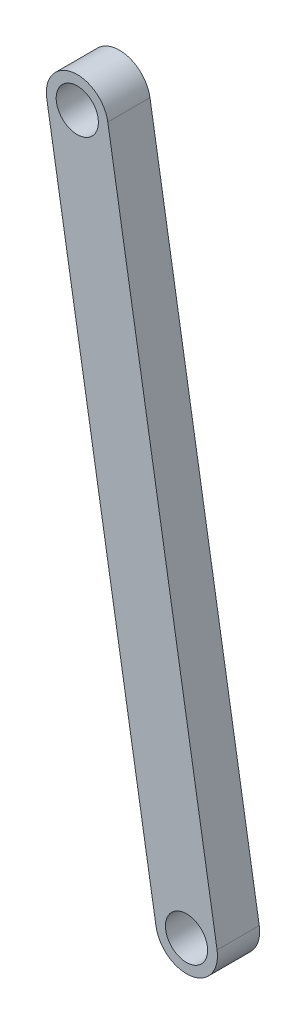
SolidWorks part; units mm, degrees
ref_plane "Plan de face" through (0, 0, 0) normal (0, 0, 1) x (1, 0, 0)
ref_plane "Plan de dessus" through (0, 0, 0) normal (0, 1, 0) x (1, 0, 0)
ref_plane "Plan de droite" through (0, 0, 0) normal (1, 0, 0) x (0, 0, -1)
sketch "Esquisse1" plane through (0, 0, 0) normal (0, 0, 1) x (1, 0, 0)
  line L0 (65.4807, 459.465) -> (146.7261, 401.1625) construction
  line L1 (0, 0) -> (7.77, -47.1) construction
  line L2 (2.1707, 0.3581) -> (9.9407, -46.7419)
  line L3 (-2.1707, -0.3581) -> (5.5993, -47.4581)
  circle A0 centre (0, 0) radius 1.5
  circle A1 centre (7.77, -47.1) radius 1.5
  arc A2 (2.1707, 0.3581) -> (-2.1707, -0.3581) centre (0, 0) ccw
  arc A3 (5.5993, -47.4581) -> (9.9407, -46.7419) centre (7.77, -47.1) ccw
  point P7 (3.885, -23.55)
extrude "Boss.-Extru.1" add sketch "Esquisse1" along normal blind 3
